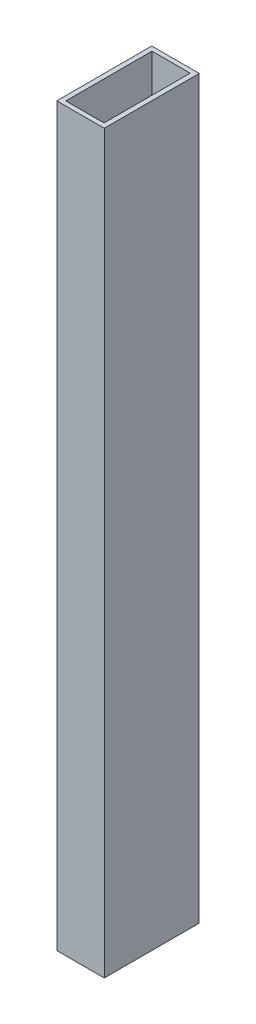
SolidWorks part; units mm, degrees
ref_plane "Front" through (0, 0, 0) normal (0, 0, 1) x (1, 0, 0)
ref_plane "Top" through (0, 0, 0) normal (0, 1, 0) x (1, 0, 0)
ref_plane "Right" through (0, 0, 0) normal (1, 0, 0) x (0, 0, -1)
sketch "Sketch1" plane through (0, 0, 0) normal (0, 1, 0) x (1, 0, 0)
  line L1 (-9.9715, -25.104) -> (15.4285, -25.104)
  line L2 (-9.9715, -25.104) -> (-9.9715, 25.696)
  line L3 (-9.9715, 25.696) -> (15.4285, 25.696)
  line L4 (15.4285, -25.104) -> (15.4285, 25.696)
  line L5 (-9.9715, -25.104) -> (15.4285, 25.696) construction
  line L6 (-9.9715, 25.696) -> (15.4285, -25.104) construction
  point P0 (2.7285, 0.296)
extrude "Boss-Extrude1" add sketch "Sketch1" along normal blind 393.7
sketch "Sketch5" plane through (0, 393.7, 0) normal (0, 1, 0) x (1, 0, 0)
  line L1 (-7.5129, -22.7318) -> (12.9079, -22.7318)
  line L2 (-7.5129, -22.7318) -> (-7.5129, 23.3858)
  line L3 (-7.5129, 23.3858) -> (12.9079, 23.3858)
  line L4 (12.9079, -22.7318) -> (12.9079, 23.3858)
  line L5 (-7.5129, -22.7318) -> (12.9079, 23.3858) construction
  line L6 (-7.5129, 23.3858) -> (12.9079, -22.7318) construction
  point P0 (2.6975, 0.327)
extrude "Cut-Extrude1" cut sketch "Sketch5" against normal blind 393.7 and the other way blind 10 from offset 0
